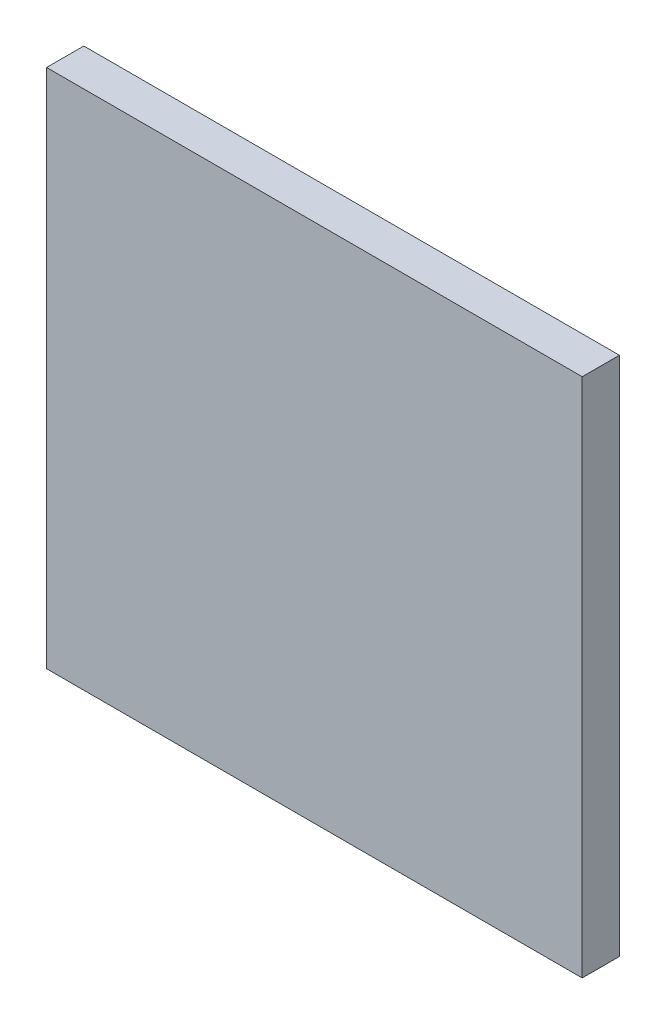
SolidWorks part; units mm, degrees
ref_plane "Plan de face" through (0, 0, 0) normal (0, 0, 1) x (1, 0, 0)
ref_plane "Plan de dessus" through (0, 0, 0) normal (0, 1, 0) x (1, 0, 0)
ref_plane "Plan de droite" through (0, 0, 0) normal (1, 0, 0) x (0, 0, -1)
sketch "Esquisse1" plane through (0, 0, 0) normal (0, 0, 1) x (1, 0, 0)
  line L1 (-36.9395, 58.3746) -> (35.0605, 58.3746)
  line L2 (-36.9395, 58.3746) -> (-36.9395, -11.6254)
  line L3 (-36.9395, -11.6254) -> (35.0605, -11.6254)
  line L4 (35.0605, 58.3746) -> (35.0605, -11.6254)
  dimension "D1" = 70
  dimension "D2" = 72
extrude "Extrusion1" add sketch "Esquisse1" along normal blind 5
